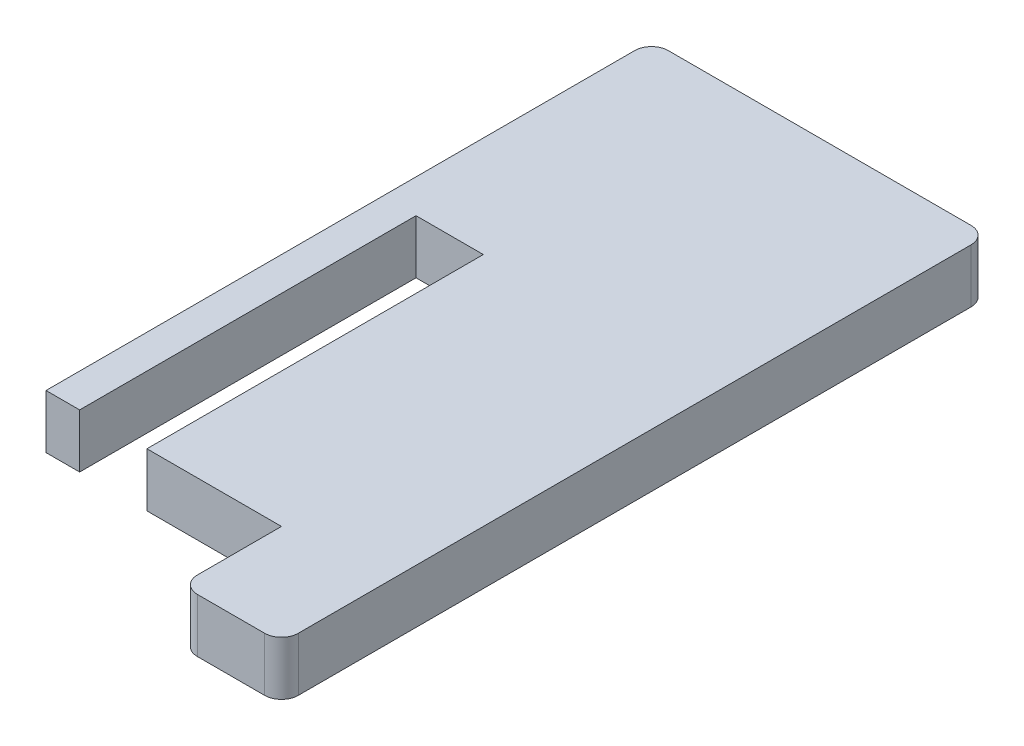
SolidWorks part; units mm, degrees
ref_plane "Front Plane" through (0, 0, 0) normal (0, 0, 1) x (1, 0, 0)
ref_plane "Top Plane" through (0, 0, 0) normal (0, 1, 0) x (1, 0, 0)
ref_plane "Right Plane" through (0, 0, 0) normal (1, 0, 0) x (0, 0, -1)
sketch "Sketch2" plane through (0, 0, 0) normal (0, 1, 0) x (1, 0, 0)
  line L0 (606.4123, -61.4484) -> (608.4123, -61.4484)
  line L2 (598.9123, -58.4484) -> (599.6623, -58.4484)
  line L3 (602.1623, -58.4484) -> (605.9123, -58.4484)
  line L5 (601.9123, -48.4484) -> (599.9123, -48.4484)
  line L6 (598.9123, -58.4484) -> (598.9123, -40.9484)
  line L7 (599.4123, -40.4484) -> (608.4123, -40.4484)
  line L8 (608.9123, -60.9484) -> (608.9123, -40.9484)
  line L10 (605.9123, -60.9484) -> (605.9123, -58.4484)
  line L38 (599.9123, -48.4484) -> (599.9123, -58.4484)
  line L39 (599.9123, -58.4484) -> (599.6623, -58.4484)
  line L41 (601.9123, -48.4484) -> (601.9123, -58.4484)
  line L42 (601.9123, -58.4484) -> (602.1623, -58.4484)
  arc A0 (599.4123, -40.4484) -> (598.9123, -40.9484) centre (599.4123, -40.9484) ccw
  arc A1 (608.4123, -61.4484) -> (608.9123, -60.9484) centre (608.4123, -60.9484) ccw
  arc A2 (608.9123, -40.9484) -> (608.4123, -40.4484) centre (608.4123, -40.9484) ccw
  arc A3 (605.9123, -60.9484) -> (606.4123, -61.4484) centre (606.4123, -60.9484) ccw
extrude "Boss-Extrude1" add sketch "Sketch2" along normal blind 1.6
